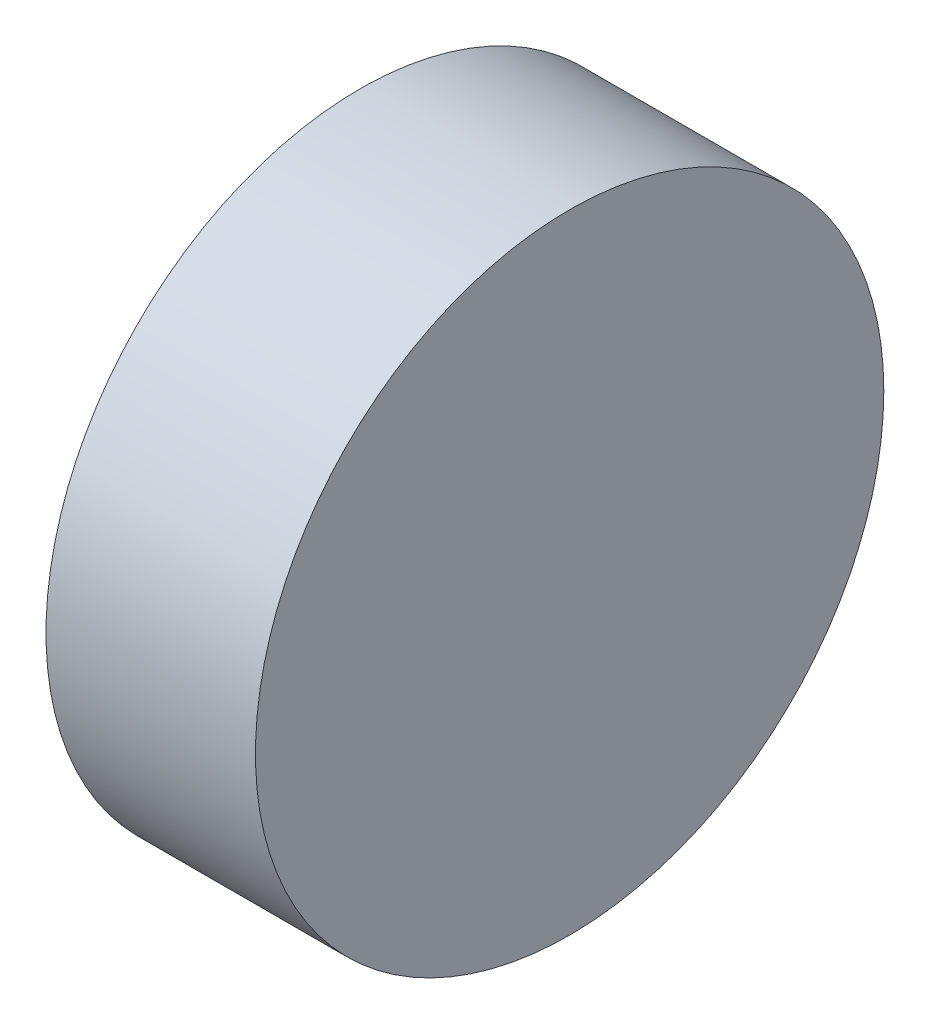
SolidWorks part; units mm, degrees
ref_plane "Front Plane" through (0, 0, 0) normal (0, 0, 1) x (1, 0, 0)
ref_plane "Top Plane" through (0, 0, 0) normal (0, 1, 0) x (1, 0, 0)
ref_plane "Right Plane" through (0, 0, 0) normal (1, 0, 0) x (0, 0, -1)
sketch "Sketch1" plane through (0, 0, 0) normal (1, 0, 0) x (0, 0, -1)
  circle A0 centre (0, 0) radius 30
  circle A1 centre (0, 0) radius 2.5
  dimension "D1" = 60
  dimension "D2" = 5
extrude "Boss-Extrude1" add sketch "Sketch1" along normal blind 10
sketch "Sketch2" plane through (10, 0, 0) normal (1, 0, 0) x (0, 0, -1)
  circle A0 centre (0, 0) radius 30
  circle A3 centre (0, 0) radius 30 construction
extrude "Boss-Extrude2" add sketch "Sketch2" along normal blind 10
